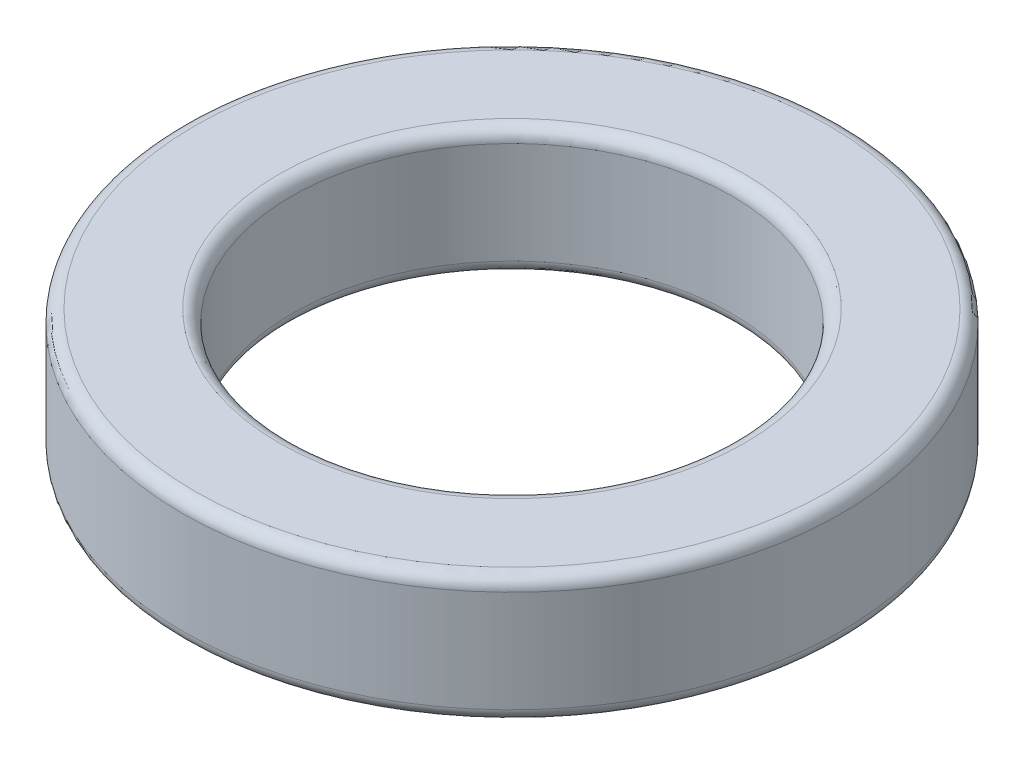
SolidWorks part; units mm, degrees
ref_plane "Спереди" through (0, 0, 0) normal (0, 0, 1) x (1, 0, 0)
ref_plane "Сверху" through (0, 0, 0) normal (0, 1, 0) x (1, 0, 0)
ref_plane "Справа" through (0, 0, 0) normal (1, 0, 0) x (0, 0, -1)
sketch "Эскиз1" plane through (0, 0, 0) normal (0, 1, 0) x (1, 0, 0)
  circle A0 centre (0, 0) radius 8.65
  circle A1 centre (0, 0) radius 12.95
  dimension "D1" = 17.3
  dimension "D2" = 25.9
extrude "Бобышка-Вытянуть1" add sketch "Эскиз1" along normal blind 5
fillet "Скругление1" radius 0.5 4 edges at (0, 0, 8.65) (0, 0, 12.95) (0, 5, 8.65) (0, 5, 12.95)
